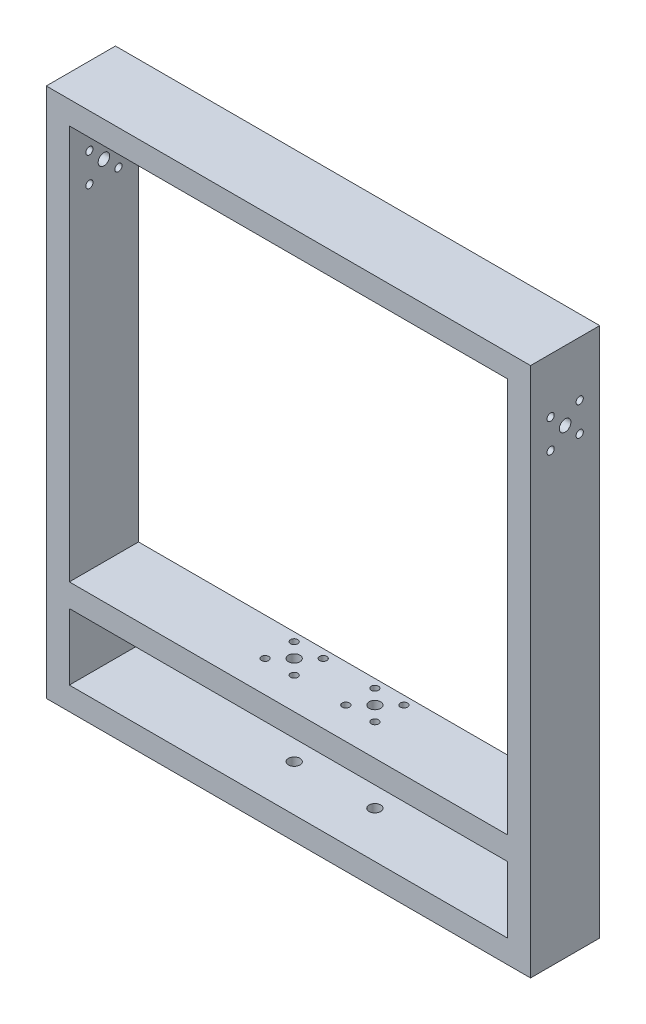
SolidWorks part; units mm, degrees
ref_plane "Plan de face" through (0, 0, 0) normal (0, 0, 1) x (1, 0, 0)
ref_plane "Plan de dessus" through (0, 0, 0) normal (0, 1, 0) x (1, 0, 0)
ref_plane "Plan de droite" through (0, 0, 0) normal (1, 0, 0) x (0, 0, -1)
sketch "Esquisse1" plane through (0, 0, 0) normal (0, 1, 0) x (1, 0, 0)
  line L0 (0, 19.05) -> (0, -19.05) construction
  line L1 (-133.35, 19.05) -> (133.35, 19.05)
  line L2 (-133.35, 19.05) -> (-133.35, -19.05)
  line L3 (-133.35, -19.05) -> (133.35, -19.05)
  line L4 (133.35, 19.05) -> (133.35, -19.05)
  line L5 (-133.35, 19.05) -> (133.35, -19.05) construction
  line L6 (-133.35, -19.05) -> (133.35, 19.05) construction
  point P0 (0, 0)
  dimension "D1" = 266.7
  dimension "D2" = 38.1
extrude "Boss.-Extru.1" add sketch "Esquisse1" along normal blind 12.7
sketch "Esquisse2" plane through (0, 12.7, 0) normal (0, 1, 0) x (1, 0, 0)
  line L0 (-133.35, -19.05) -> (133.35, -19.05) construction
  line L1 (-133.35, 19.05) -> (-120.65, 19.05)
  line L2 (-133.35, 19.05) -> (-133.35, -19.05)
  line L3 (-133.35, -19.05) -> (-120.65, -19.05)
  line L4 (-120.65, 19.05) -> (-120.65, -19.05)
  line L5 (-133.35, 19.05) -> (-120.65, -19.05) construction
  line L6 (-133.35, -19.05) -> (-120.65, 19.05) construction
  line L7 (0, 0) -> (0, 19.05) construction
  line L8 (133.35, 19.05) -> (-133.35, 19.05) construction
  line L9 (133.35, -19.05) -> (120.65, 19.05) construction
  line L10 (133.35, 19.05) -> (120.65, -19.05) construction
  line L11 (120.65, 19.05) -> (120.65, -19.05)
  line L12 (133.35, -19.05) -> (120.65, -19.05)
  line L13 (133.35, 19.05) -> (133.35, -19.05)
  line L14 (133.35, 19.05) -> (120.65, 19.05)
  point P4 (-127, 0)
  point P17 (127, 0)
  dimension "D1" = 12.7
extrude "Boss.-Extru.2" add sketch "Esquisse2" along normal blind 279.4
sketch "Esquisse3" plane through (0, 12.7, 0) normal (0, 1, 0) x (1, 0, 0)
  line L0 (0, 0) -> (0, 19.05) construction
  line L1 (120.65, 19.05) -> (-120.65, 19.05) construction
  circle A0 centre (-22.225, 6.35) radius 3.175
  dimension "D3" = 6.35
  dimension "D1" = 22.225
  dimension "D2" = 12.7
extrude "Enlèv. mat.-Extru.1" cut sketch "Esquisse3" against normal through all contours A0
sketch "Esquisse4" plane through (0, 12.7, 0) normal (0, 1, 0) x (1, 0, 0)
  line L0 (120.65, 19.05) -> (-120.65, 19.05) construction
  circle A0 centre (22.225, 6.35) radius 3.175
  circle A1 centre (-22.225, 6.35) radius 3.175 construction
  dimension "D1" = 12.7
  dimension "D2" = 22.225
extrude "Enlèv. mat.-Extru.2" cut sketch "Esquisse4" against normal through all
sketch "Esquisse5" plane through (-120.65, 0, 0) normal (1, 0, 0) x (0, 0, -1)
  line L0 (19.05, 292.1) -> (19.05, 12.7) construction
  line L1 (19.05, 61.9125) -> (-19.05, 61.9125)
  line L2 (19.05, 61.9125) -> (19.05, 49.2125)
  line L3 (19.05, 49.2125) -> (-19.05, 49.2125)
  line L4 (-19.05, 61.9125) -> (-19.05, 49.2125)
  line L5 (19.05, 61.9125) -> (-19.05, 49.2125) construction
  line L6 (19.05, 49.2125) -> (-19.05, 61.9125) construction
  line L7 (-19.05, 12.7) -> (19.05, 12.7) construction
  point P4 (0, 55.5625)
  dimension "D1" = 12.7
  dimension "D2" = 49.2125
  dimension "D3" = 38.1
extrude "Boss.-Extru.3" add sketch "Esquisse5" along normal up to next
sketch "Esquisse6" plane through (-120.65, 0, 0) normal (1, 0, 0) x (0, 0, -1)
  line L0 (-19.05, 292.1) -> (-19.05, 61.9125) construction
  line L1 (19.05, 292.1) -> (-19.05, 292.1)
  line L2 (19.05, 292.1) -> (19.05, 279.4)
  line L3 (19.05, 279.4) -> (-19.05, 279.4)
  line L4 (-19.05, 292.1) -> (-19.05, 279.4)
  line L5 (19.05, 292.1) -> (-19.05, 279.4) construction
  line L6 (19.05, 279.4) -> (-19.05, 292.1) construction
  point P4 (0, 285.75)
  dimension "D1" = 12.7
extrude "Boss.-Extru.4" add sketch "Esquisse6" along normal up to next
sketch "Esquisse9" plane through (-133.35, 0, 0) normal (-1, 0, 0) x (0, 0, 1)
  line L0 (0, 292.1) -> (0, 0) construction
  line L1 (-19.05, 292.1) -> (19.05, 292.1) construction
  circle A0 centre (0, 254) radius 3.175
  dimension "D1" = 6.35
  dimension "D2" = 254
extrude "Enlèv. mat.-Extru.3" cut sketch "Esquisse9" against normal through all
sketch "Esquisse10" plane through (-133.35, 0, 0) normal (-1, 0, 0) x (0, 0, 1)
  line L1 (-8, 262) -> (8, 262) construction
  line L2 (-8, 262) -> (-8, 246) construction
  line L3 (-8, 246) -> (8, 246) construction
  line L4 (8, 262) -> (8, 246) construction
  line L5 (-8, 262) -> (8, 246) construction
  line L6 (-8, 246) -> (8, 262) construction
  circle A0 centre (8, 262) radius 2
  circle A1 centre (-8, 262) radius 2
  circle A2 centre (-8, 246) radius 2
  circle A3 centre (8, 246) radius 2
  point P8 (0, 254)
  dimension "D1" = 4
  dimension "D2" = 16
  dimension "D3" = 16
extrude "Enlèv. mat.-Extru.4" cut sketch "Esquisse10" against normal through all
sketch "Esquisse12" plane through (-133.35, 0, 0) normal (-1, 0, 0) x (0, 0, 1)
  circle A0 centre (8, 262) radius 4.7625
  circle A1 centre (-8, 262) radius 4.7625
  circle A2 centre (-8, 246) radius 4.7625
  circle A3 centre (8, 246) radius 4.7625
  dimension "D1" = 9.525
extrude "Enlèv. mat.-Extru.5" cut sketch "Esquisse12" against normal blind 4.7625
sketch "Esquisse13" plane through (120.65, 0, 0) normal (1, 0, 0) x (0, 0, -1)
  circle A0 centre (8, 262) radius 4.7625
  circle A1 centre (8, 246) radius 4.7625
  circle A2 centre (-8, 246) radius 4.7625
  circle A3 centre (-8, 262) radius 4.7625
  dimension "D1" = 9.525
extrude "Enlèv. mat.-Extru.6" cut sketch "Esquisse13" along normal blind 4.7625
sketch "Esquisse17" plane through (0, 0, 0) normal (0, -1, 0) x (1, 0, 0)
  circle A0 centre (22.225, -6.35) radius 3.175 construction
  circle A1 centre (-22.225, -6.35) radius 3.175 construction
  circle A2 centre (22.225, -6.35) radius 3.175
  circle A3 centre (-22.225, -6.35) radius 3.175
extrude "Enlèv. mat.-Extru.7" cut sketch "Esquisse17" against normal blind 76.2
sketch "Esquisse18" plane through (0, 61.9125, 0) normal (0, 1, 0) x (1, 0, 0)
  line L1 (30.225, -1.65) -> (14.225, -1.65) construction
  line L2 (30.225, -1.65) -> (30.225, 14.35) construction
  line L3 (30.225, 14.35) -> (14.225, 14.35) construction
  line L4 (14.225, -1.65) -> (14.225, 14.35) construction
  line L5 (30.225, -1.65) -> (14.225, 14.35) construction
  line L6 (30.225, 14.35) -> (14.225, -1.65) construction
  line L7 (-14.225, -1.65) -> (-30.225, -1.65) construction
  line L8 (-14.225, -1.65) -> (-14.225, 14.35) construction
  line L9 (-14.225, 14.35) -> (-30.225, 14.35) construction
  line L10 (-30.225, -1.65) -> (-30.225, 14.35) construction
  line L11 (-14.225, -1.65) -> (-30.225, 14.35) construction
  line L12 (-14.225, 14.35) -> (-30.225, -1.65) construction
  circle A0 centre (14.225, -1.65) radius 2
  circle A1 centre (14.225, 14.35) radius 2
  circle A2 centre (30.225, 14.35) radius 2
  circle A3 centre (30.225, -1.65) radius 2
  circle A4 centre (-14.225, -1.65) radius 2
  circle A5 centre (-30.225, -1.65) radius 2
  circle A6 centre (-30.225, 14.35) radius 2
  circle A7 centre (-14.225, 14.35) radius 2
  point P0 (22.225, 6.35)
  point P10 (-22.225, 6.35)
  dimension "D3" = 4
  dimension "D6" = 4
  dimension "D1" = 16
  dimension "D2" = 16
  dimension "D4" = 16
  dimension "D5" = 16
extrude "Enlèv. mat.-Extru.8" cut sketch "Esquisse18" against normal blind 25.4
sketch "Esquisse20" plane through (0, 49.2125, 0) normal (0, -1, 0) x (1, 0, 0)
  circle A0 centre (30.225, -14.35) radius 3.9687
  circle A1 centre (14.225, -14.35) radius 3.9688
  circle A2 centre (14.225, 1.65) radius 3.9688
  circle A3 centre (30.225, 1.65) radius 3.9687
  circle A4 centre (-14.225, -14.35) radius 3.9688
  circle A5 centre (-30.225, -14.35) radius 3.9688
  circle A6 centre (-30.225, 1.65) radius 3.9688
  circle A7 centre (-14.225, 1.65) radius 3.9688
  dimension "D1" = 7.9375
extrude "Enlèv. mat.-Extru.9" cut sketch "Esquisse20" against normal blind 4.7625
